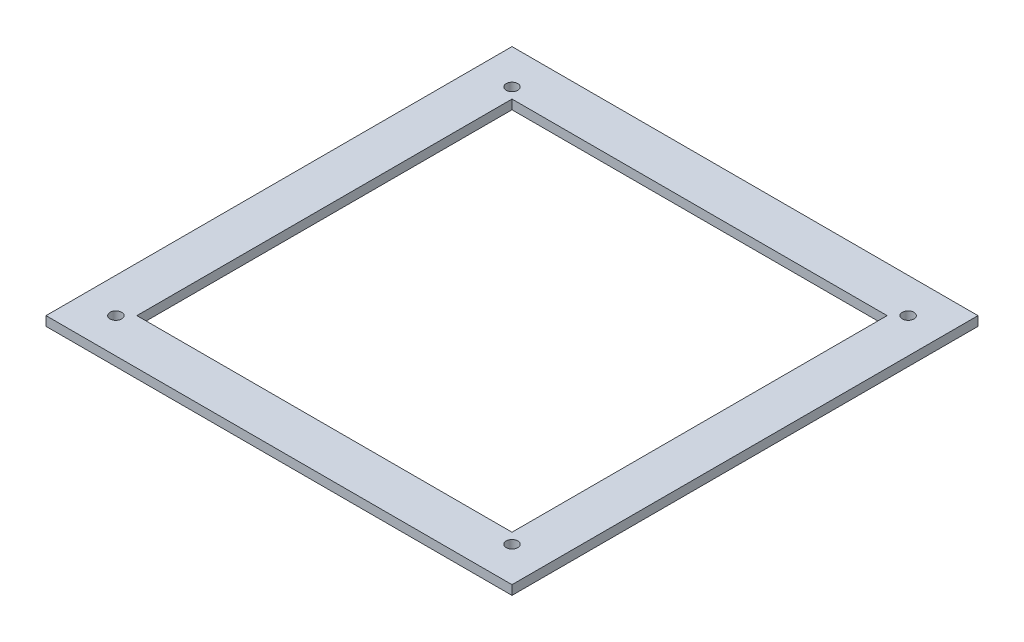
SolidWorks part; units mm, degrees
ref_plane "Alzado" through (0, 0, 0) normal (0, 0, 1) x (1, 0, 0)
ref_plane "Planta" through (0, 0, 0) normal (0, 1, 0) x (1, 0, 0)
ref_plane "Vista lateral" through (0, 0, 0) normal (1, 0, 0) x (0, 0, -1)
sketch "Croquis1" plane through (0, 0, 0) normal (0, 1, 0) x (1, 0, 0)
  line L0 (100, 15) -> (100, 0) construction
  line L1 (0, 0) -> (200, 0)
  line L2 (0, 0) -> (0, 200)
  line L3 (0, 200) -> (200, 200)
  line L4 (200, 0) -> (200, 200)
  line L5 (15, 15) -> (185, 15) construction
  line L6 (15, 15) -> (15, 185) construction
  line L7 (15, 185) -> (185, 185) construction
  line L8 (185, 15) -> (185, 185) construction
  line L9 (185, 100) -> (200, 100) construction
  circle A0 centre (15, 185) radius 2.5
  circle A1 centre (185, 185) radius 2.5
  circle A2 centre (185, 15) radius 2.5
  circle A3 centre (15, 15) radius 2.5
  dimension "D3" = 5
  dimension "D1" = 200
  dimension "D2" = 170
extrude "Saliente-Extruir1" add sketch "Croquis1" along normal blind 4
sketch "Croquis2" plane through (0, 4, 0) normal (0, 1, 0) x (1, 0, 0)
  line L0 (0, 200) -> (200, 0) construction
  line L2 (21, 21) -> (179, 21)
  line L3 (21, 21) -> (21, 179)
  line L4 (21, 179) -> (179, 179)
  line L5 (179, 21) -> (179, 179)
  line L6 (21, 21) -> (179, 179) construction
  line L7 (21, 179) -> (179, 21) construction
  point P4 (100, 100)
  dimension "D1" = 158
extrude "Cortar-Extruir1" cut sketch "Croquis2" against normal blind 10
sketch "Croquis3" plane through (0, 4, 0) normal (0, 1, 0) x (1, 0, 0)
  line L8 (19.5, 180.5) -> (19.5, 19.5)
  line L9 (19.5, 19.5) -> (180.5, 19.5)
  line L10 (180.5, 19.5) -> (180.5, 180.5)
  line L11 (180.5, 180.5) -> (19.5, 180.5)
  line L12 (19.5, 180.5) -> (19.5, 19.5)
  line L13 (19.5, 19.5) -> (180.5, 19.5)
  line L14 (180.5, 19.5) -> (180.5, 180.5)
  line L15 (180.5, 180.5) -> (19.5, 180.5)
  dimension "D1" = 1.5
extrude "Cortar-Extruir2" cut sketch "Croquis3" against normal blind 10
